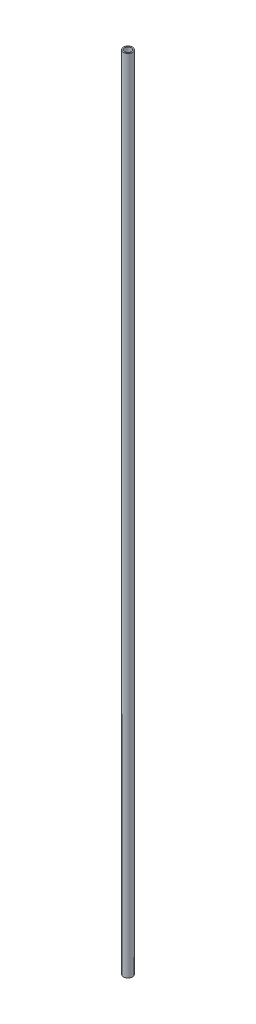
SolidWorks part; units mm, degrees
ref_plane "Front Plane" through (0, 0, 0) normal (0, 0, 1) x (1, 0, 0)
ref_plane "Top Plane" through (0, 0, 0) normal (0, 1, 0) x (1, 0, 0)
ref_plane "Right Plane" through (0, 0, 0) normal (1, 0, 0) x (0, 0, -1)
sketch "Szkic1" plane through (0, 0, 0) normal (0, 1, 0) x (1, 0, 0)
  circle A0 centre (0, 0) radius 4
  circle A1 centre (0, 0) radius 3
  dimension "D1" = 8
  dimension "D2" = 6
extrude "Dodanie-wyciągnięcie1" add sketch "Szkic1" along normal blind 700
